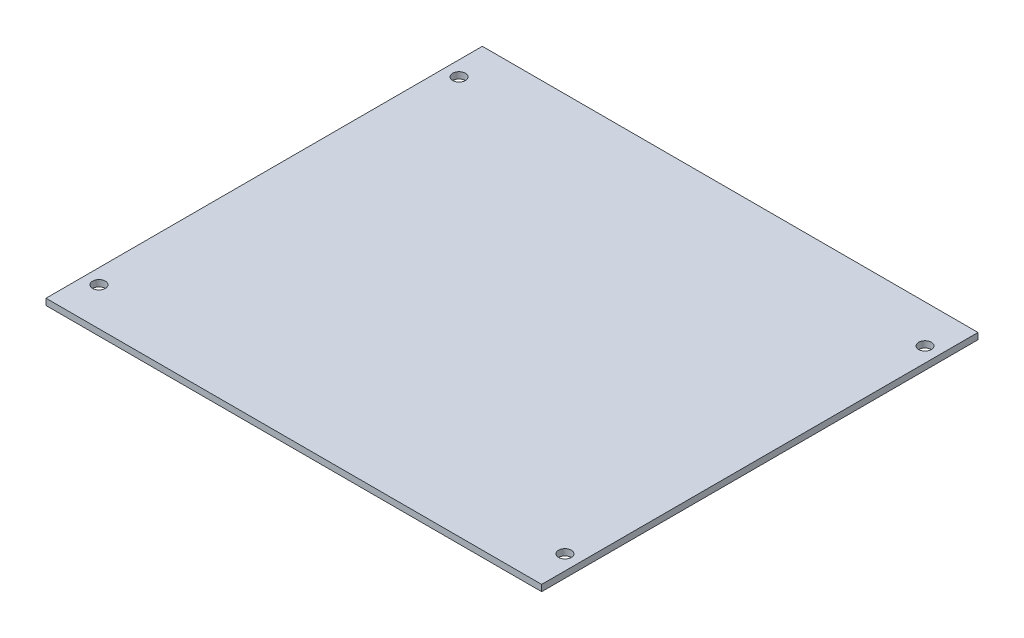
SolidWorks part; units mm, degrees
ref_plane "Спереди" through (0, 0, 0) normal (0, 0, 1) x (1, 0, 0)
ref_plane "Сверху" through (0, 0, 0) normal (0, 1, 0) x (1, 0, 0)
ref_plane "Справа" through (0, 0, 0) normal (1, 0, 0) x (0, 0, -1)
sketch "Эскиз1" plane through (0, 0, 0) normal (0, 1, 0) x (1, 0, 0)
  line L1 (-58.5, 51.5) -> (58.5, 51.5)
  line L2 (-58.5, 51.5) -> (-58.5, -51.5)
  line L3 (-58.5, -51.5) -> (58.5, -51.5)
  line L4 (58.5, 51.5) -> (58.5, -51.5)
  line L5 (-58.5, 51.5) -> (58.5, -51.5) construction
  line L6 (-58.5, -51.5) -> (58.5, 51.5) construction
  line L7 (-55, 42.5) -> (55, 42.5) construction
  line L8 (-55, 42.5) -> (-55, -42.5) construction
  line L9 (-55, -42.5) -> (55, -42.5) construction
  line L10 (55, 42.5) -> (55, -42.5) construction
  line L11 (-55, 42.5) -> (55, -42.5) construction
  line L12 (-55, -42.5) -> (55, 42.5) construction
  circle A0 centre (-55, 42.5) radius 1.5
  circle A1 centre (55, 42.5) radius 1.5
  circle A2 centre (55, -42.5) radius 1.5
  circle A3 centre (-55, -42.5) radius 1.5
  point P0 (0, 0)
  point P6 (0, 0)
  dimension "D5" = 3
  dimension "D1" = 117
  dimension "D2" = 103
  dimension "D3" = 110
  dimension "D4" = 85
extrude "Бобышка-Вытянуть1" add sketch "Эскиз1" along normal blind 1.5
